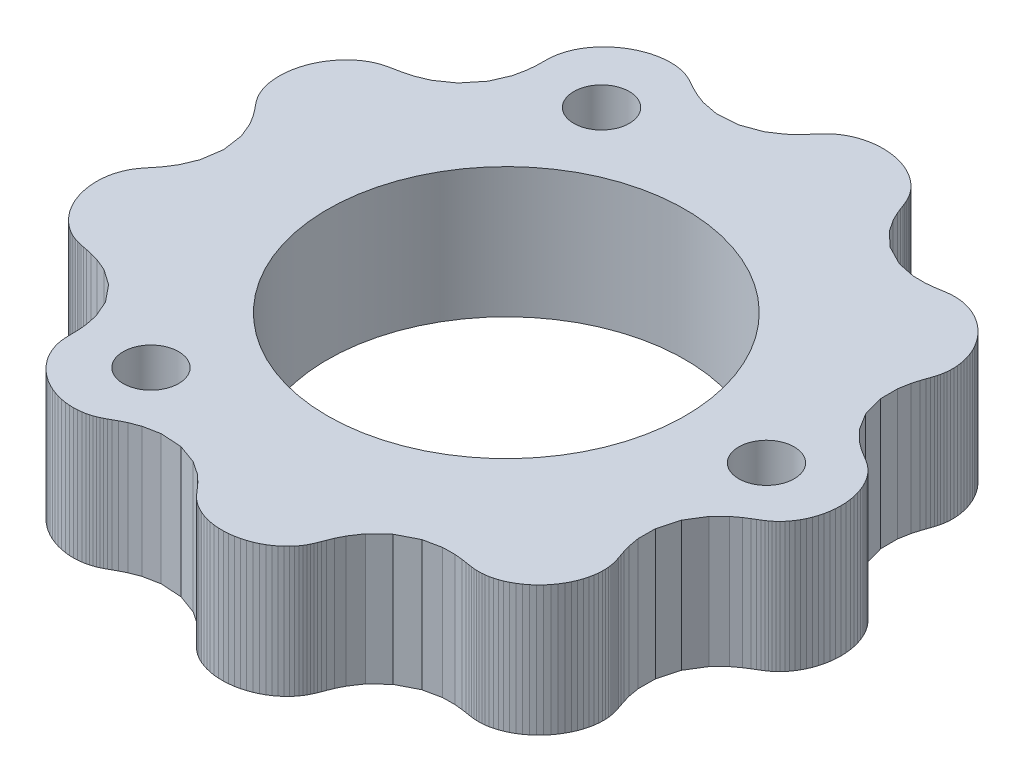
SolidWorks part; units mm, degrees
ref_plane "Front" through (0, 0, 0) normal (0, 0, 1) x (1, 0, 0)
ref_plane "Top" through (0, 0, 0) normal (0, 1, 0) x (1, 0, 0)
ref_plane "Right" through (0, 0, 0) normal (1, 0, 0) x (0, 0, -1)
sketch "Sketch1" plane through (0, 0, 0) normal (0, 1, 0) x (1, 0, 0)
  line L0 (15.113, 0) -> (15.1037, 0.2524) construction
  line L1 (15.1037, 0.2524) -> (15.0761, 0.5014) construction
  line L2 (15.0761, 0.5014) -> (15.0311, 0.744) construction
  line L3 (15.0311, 0.744) -> (14.9699, 0.9771) construction
  line L4 (14.9699, 0.9771) -> (14.8944, 1.198) construction
  line L5 (14.8944, 1.198) -> (14.8069, 1.4044) construction
  line L6 (14.8069, 1.4044) -> (14.7097, 1.5946) construction
  line L7 (14.7097, 1.5946) -> (14.6056, 1.7674) construction
  line L8 (14.6056, 1.7674) -> (14.4973, 1.922) construction
  line L9 (14.4973, 1.922) -> (14.3874, 2.0586) construction
  line L10 (14.3874, 2.0586) -> (14.2779, 2.1778) construction
  line L11 (14.2779, 2.1778) -> (14.1706, 2.2811) construction
  line L12 (14.1706, 2.2811) -> (14.0658, 2.3708) construction
  line L13 (14.0658, 2.3708) -> (13.9626, 2.4499) construction
  line L14 (13.9626, 2.4499) -> (13.8577, 2.5227) construction
  line L15 (13.8577, 2.5227) -> (13.7444, 2.5952) construction
  line L16 (13.7444, 2.5952) -> (13.6106, 2.6762) construction
  line L17 (13.6106, 2.6762) -> (13.4356, 2.7811) construction
  line L18 (13.4356, 2.7811) -> (13.1874, 2.9387) construction
  line L19 (13.1874, 2.9387) -> (12.8245, 3.2087) construction
  line L20 (12.8245, 3.2087) -> (12.3314, 3.7011) construction
  line L21 (12.3314, 3.7011) -> (11.8258, 4.5171) construction
  line L22 (11.8258, 4.5171) -> (11.5537, 5.5075) construction
  line L23 (11.5537, 5.5075) -> (11.55, 6.3294) construction
  line L24 (11.55, 6.3294) -> (11.6479, 6.8716) construction
  line L25 (11.6479, 6.8716) -> (11.7462, 7.2119) construction
  line L26 (11.7462, 7.2119) -> (11.8222, 7.4368) construction
  line L27 (11.8222, 7.4368) -> (11.879, 7.6008) construction
  line L28 (11.879, 7.6008) -> (11.9232, 7.7357) construction
  line L29 (11.9232, 7.7357) -> (11.9594, 7.8598) construction
  line L30 (11.9594, 7.8598) -> (11.9899, 7.9842) construction
  line L31 (11.9899, 7.9842) -> (12.0151, 8.1157) construction
  line L32 (12.0151, 8.1157) -> (12.0342, 8.2582) construction
  line L33 (12.0342, 8.2582) -> (12.0455, 8.4138) construction
  line L34 (12.0455, 8.4138) -> (12.047, 8.5831) construction
  line L35 (12.047, 8.5831) -> (12.0365, 8.7657) construction
  line L36 (12.0365, 8.7657) -> (12.012, 8.9602) construction
  line L37 (12.012, 8.9602) -> (11.9717, 9.1647) construction
  line L38 (11.9717, 9.1647) -> (11.9141, 9.3767) construction
  line L39 (11.9141, 9.3767) -> (11.8383, 9.5933) construction
  line L40 (11.8383, 9.5933) -> (11.7436, 9.8115) construction
  line L41 (11.7436, 9.8115) -> (11.6304, 10.0281) construction
  line L42 (11.6304, 10.0281) -> (11.4991, 10.2398) construction
  line L43 (11.4991, 10.2398) -> (11.3509, 10.4435) construction
  line L44 (11.3509, 10.4435) -> (11.1876, 10.6365) construction
  line L45 (11.1876, 10.6365) -> (11.0114, 10.8162) construction
  line L46 (11.0114, 10.8162) -> (10.8247, 10.9805) construction
  line L47 (10.8247, 10.9805) -> (10.6304, 11.1277) construction
  line L48 (10.6304, 11.1277) -> (10.4316, 11.2567) construction
  line L49 (10.4316, 11.2567) -> (10.2314, 11.3669) construction
  line L50 (10.2314, 11.3669) -> (10.033, 11.4584) construction
  line L51 (10.033, 11.4584) -> (9.8393, 11.5316) construction
  line L52 (9.8393, 11.5316) -> (9.6529, 11.5876) construction
  line L53 (9.6529, 11.5876) -> (9.4761, 11.628) construction
  line L54 (9.4761, 11.628) -> (9.3104, 11.6545) construction
  line L55 (9.3104, 11.6545) -> (9.1565, 11.6691) construction
  line L56 (9.1565, 11.6691) -> (9.0141, 11.6741) construction
  line L57 (9.0141, 11.6741) -> (8.8811, 11.6714) construction
  line L58 (8.8811, 11.6714) -> (8.7536, 11.6623) construction
  line L59 (8.7536, 11.6623) -> (8.6244, 11.6475) construction
  line L60 (8.6244, 11.6475) -> (8.4816, 11.6267) construction
  line L61 (8.4816, 11.6267) -> (8.305, 11.5984) construction
  line L62 (8.305, 11.5984) -> (8.0605, 11.5618) construction
  line L63 (8.0605, 11.5618) -> (7.6906, 11.5252) construction
  line L64 (7.6906, 11.5252) -> (7.1123, 11.532) construction
  line L65 (7.1123, 11.532) -> (6.2778, 11.7054) construction
  line L66 (6.2778, 11.7054) -> (5.3573, 12.1787) construction
  line L67 (5.3573, 12.1787) -> (4.6782, 12.8227) construction
  line L68 (4.6782, 12.8227) -> (4.3077, 13.3763) construction
  line L69 (4.3077, 13.3763) -> (4.1189, 13.7632) construction
  line L70 (4.1189, 13.7632) -> (4.013, 14.0236) construction
  line L71 (4.013, 14.0236) -> (3.9428, 14.2077) construction
  line L72 (3.9428, 14.2077) -> (3.8871, 14.3502) construction
  line L73 (3.8871, 14.3502) -> (3.8355, 14.4729) construction
  line L74 (3.8355, 14.4729) -> (3.7815, 14.5885) construction
  line L75 (3.7815, 14.5885) -> (3.7206, 14.7041) construction
  line L76 (3.7206, 14.7041) -> (3.6492, 14.8234) construction
  line L77 (3.6492, 14.8234) -> (3.5645, 14.9476) construction
  line L78 (3.5645, 14.9476) -> (3.4642, 15.0766) construction
  line L79 (3.4642, 15.0766) -> (3.3469, 15.2088) construction
  line L80 (3.3469, 15.2088) -> (3.2113, 15.3424) construction
  line L81 (3.2113, 15.3424) -> (3.0572, 15.4746) construction
  line L82 (3.0572, 15.4746) -> (2.8848, 15.6027) construction
  line L83 (2.8848, 15.6027) -> (2.6948, 15.7239) construction
  line L84 (2.6948, 15.7239) -> (2.4886, 15.8353) construction
  line L85 (2.4886, 15.8353) -> (2.2682, 15.9346) construction
  line L86 (2.2682, 15.9346) -> (2.036, 16.0194) construction
  line L87 (2.036, 16.0194) -> (1.7946, 16.0879) construction
  line L88 (1.7946, 16.0879) -> (1.5472, 16.1389) construction
  line L89 (1.5472, 16.1389) -> (1.2969, 16.1715) construction
  line L90 (1.2969, 16.1715) -> (1.047, 16.1855) construction
  line L91 (1.047, 16.1855) -> (0.8009, 16.1813) construction
  line L92 (0.8009, 16.1813) -> (0.5617, 16.1596) construction
  line L93 (0.5617, 16.1596) -> (0.3322, 16.1219) construction
  line L94 (0.3322, 16.1219) -> (0.1152, 16.0701) construction
  line L95 (0.1152, 16.0701) -> (-0.0873, 16.0062) construction
  line L96 (-0.0873, 16.0062) -> (-0.2736, 15.9328) construction
  line L97 (-0.2736, 15.9328) -> (-0.4428, 15.8523) construction
  line L98 (-0.4428, 15.8523) -> (-0.5944, 15.7674) construction
  line L99 (-0.5944, 15.7674) -> (-0.729, 15.6802) construction
  line L100 (-0.729, 15.6802) -> (-0.8477, 15.5923) construction
  line L101 (-0.8477, 15.5923) -> (-0.9528, 15.5047) construction
  line L102 (-0.9528, 15.5047) -> (-1.0477, 15.4167) construction
  line L103 (-1.0477, 15.4167) -> (-1.1374, 15.3255) construction
  line L104 (-1.1374, 15.3255) -> (-1.2291, 15.2251) construction
  line L105 (-1.2291, 15.2251) -> (-1.3345, 15.1043) construction
  line L106 (-1.3345, 15.1043) -> (-1.4732, 14.9447) construction
  line L107 (-1.4732, 14.9447) -> (-1.682, 14.7187) construction
  line L108 (-1.682, 14.7187) -> (-2.0315, 14.3967) construction
  line L109 (-2.0315, 14.3967) -> (-2.6365, 13.9915) construction
  line L110 (-2.6365, 13.9915) -> (-3.5585, 13.6551) construction
  line L111 (-3.5585, 13.6551) -> (-4.5719, 13.5925) construction
  line L112 (-4.5719, 13.5925) -> (-5.3478, 13.7456) construction
  line L113 (-5.3478, 13.7456) -> (-5.8372, 13.9345) construction
  line L114 (-5.8372, 13.9345) -> (-6.1394, 14.0854) construction
  line L115 (-6.1394, 14.0854) -> (-6.3393, 14.1953) construction
  line L116 (-6.3393, 14.1953) -> (-6.4869, 14.2772) construction
  line L117 (-6.4869, 14.2772) -> (-6.6103, 14.3428) construction
  line L118 (-6.6103, 14.3428) -> (-6.726, 14.3992) construction
  line L119 (-6.726, 14.3992) -> (-6.8438, 14.4504) construction
  line L120 (-6.8438, 14.4504) -> (-6.9701, 14.4976) construction
  line L121 (-6.9701, 14.4976) -> (-7.1086, 14.5406) construction
  line L122 (-7.1086, 14.5406) -> (-7.2615, 14.5781) construction
  line L123 (-7.2615, 14.5781) -> (-7.4297, 14.608) construction
  line L124 (-7.4297, 14.608) -> (-7.6129, 14.6282) construction
  line L125 (-7.6129, 14.6282) -> (-7.8102, 14.6364) construction
  line L126 (-7.8102, 14.6364) -> (-8.0199, 14.6306) construction
  line L127 (-8.0199, 14.6306) -> (-8.2397, 14.6088) construction
  line L128 (-8.2397, 14.6088) -> (-8.4669, 14.5697) construction
  line L129 (-8.4669, 14.5697) -> (-8.6986, 14.5124) construction
  line L130 (-8.6986, 14.5124) -> (-8.9315, 14.4364) construction
  line L131 (-8.9315, 14.4364) -> (-9.1623, 14.3418) construction
  line L132 (-9.1623, 14.3418) -> (-9.388, 14.2293) construction
  line L133 (-9.388, 14.2293) -> (-9.6053, 14.1003) construction
  line L134 (-9.6053, 14.1003) -> (-9.8115, 13.9564) construction
  line L135 (-9.8115, 13.9564) -> (-10.0041, 13.7997) construction
  line L136 (-10.0041, 13.7997) -> (-10.1809, 13.633) construction
  line L137 (-10.1809, 13.633) -> (-10.3405, 13.4589) construction
  line L138 (-10.3405, 13.4589) -> (-10.4818, 13.2806) construction
  line L139 (-10.4818, 13.2806) -> (-10.6042, 13.1011) construction
  line L140 (-10.6042, 13.1011) -> (-10.7079, 12.9234) construction
  line L141 (-10.7079, 12.9234) -> (-10.7935, 12.7502) construction
  line L142 (-10.7935, 12.7502) -> (-10.8621, 12.5839) construction
  line L143 (-10.8621, 12.5839) -> (-10.9154, 12.4264) construction
  line L144 (-10.9154, 12.4264) -> (-10.9551, 12.2785) construction
  line L145 (-10.9551, 12.2785) -> (-10.9837, 12.1401) construction
  line L146 (-10.9837, 12.1401) -> (-11.0031, 12.0093) construction
  line L147 (-11.0031, 12.0093) -> (-11.0156, 11.8823) construction
  line L148 (-11.0156, 11.8823) -> (-11.0231, 11.7516) construction
  line L149 (-11.0231, 11.7516) -> (-11.0271, 11.6047) construction
  line L150 (-11.0271, 11.6047) -> (-11.0299, 11.4203) construction
  line L151 (-11.0299, 11.4203) -> (-11.0374, 11.1626) construction
  line L152 (-11.0374, 11.1626) -> (-11.0704, 10.7738) construction
  line L153 (-11.0704, 10.7738) -> (-11.193, 10.1795) construction
  line L154 (-11.193, 10.1795) -> (-11.5414, 9.3696) construction
  line L155 (-11.5414, 9.3696) -> (-12.1963, 8.5629) construction
  line L156 (-12.1963, 8.5629) -> (-12.9426, 8.0428) construction
  line L157 (-12.9426, 8.0428) -> (-13.5295, 7.7974) construction
  line L158 (-13.5295, 7.7974) -> (-13.9245, 7.6885) construction
  line L159 (-13.9245, 7.6885) -> (-14.1879, 7.6331) construction
  line L160 (-14.1879, 7.6331) -> (-14.3749, 7.5972) construction
  line L161 (-14.3749, 7.5972) -> (-14.5218, 7.5675) construction
  line L162 (-14.5218, 7.5675) -> (-14.6503, 7.5377) construction
  line L163 (-14.6503, 7.5377) -> (-14.7733, 7.504) construction
  line L164 (-14.7733, 7.504) -> (-14.8982, 7.4631) construction
  line L165 (-14.8982, 7.4631) -> (-15.0288, 7.4122) construction
  line L166 (-15.0288, 7.4122) -> (-15.1667, 7.3489) construction
  line L167 (-15.1667, 7.3489) -> (-15.3119, 7.2709) construction
  line L168 (-15.3119, 7.2709) -> (-15.4631, 7.1764) construction
  line L169 (-15.4631, 7.1764) -> (-15.6185, 7.064) construction
  line L170 (-15.6185, 7.064) -> (-15.7755, 6.9331) construction
  line L171 (-15.7755, 6.9331) -> (-15.9313, 6.7835) construction
  line L172 (-15.9313, 6.7835) -> (-16.0831, 6.6154) construction
  line L173 (-16.0831, 6.6154) -> (-16.2277, 6.4298) construction
  line L174 (-16.2277, 6.4298) -> (-16.3625, 6.2284) construction
  line L175 (-16.3625, 6.2284) -> (-16.4848, 6.0129) construction
  line L176 (-16.4848, 6.0129) -> (-16.5925, 5.786) construction
  line L177 (-16.5925, 5.786) -> (-16.6838, 5.5503) construction
  line L178 (-16.6838, 5.5503) -> (-16.7573, 5.309) construction
  line L179 (-16.7573, 5.309) -> (-16.8125, 5.0653) construction
  line L180 (-16.8125, 5.0653) -> (-16.849, 4.8224) construction
  line L181 (-16.849, 4.8224) -> (-16.8672, 4.5837) construction
  line L182 (-16.8672, 4.5837) -> (-16.8681, 4.3522) construction
  line L183 (-16.8681, 4.3522) -> (-16.853, 4.1307) construction
  line L184 (-16.853, 4.1307) -> (-16.8238, 3.9216) construction
  line L185 (-16.8238, 3.9216) -> (-16.7826, 3.7271) construction
  line L186 (-16.7826, 3.7271) -> (-16.7318, 3.5483) construction
  line L187 (-16.7318, 3.5483) -> (-16.6738, 3.3861) construction
  line L188 (-16.6738, 3.3861) -> (-16.6108, 3.2402) construction
  line L189 (-16.6108, 3.2402) -> (-16.5447, 3.1096) construction
  line L190 (-16.5447, 3.1096) -> (-16.4764, 2.9922) construction
  line L191 (-16.4764, 2.9922) -> (-16.4059, 2.8843) construction
  line L192 (-16.4059, 2.8843) -> (-16.331, 2.7802) construction
  line L193 (-16.331, 2.7802) -> (-16.2466, 2.6713) construction
  line L194 (-16.2466, 2.6713) -> (-16.1432, 2.5436) construction
  line L195 (-16.1432, 2.5436) -> (-16.0053, 2.3728) construction
  line L196 (-16.0053, 2.3728) -> (-15.8117, 2.1151) construction
  line L197 (-15.8117, 2.1151) -> (-15.5478, 1.6912) construction
  line L198 (-15.5478, 1.6912) -> (-15.2569, 0.9896) construction
  line L199 (-15.2569, 0.9896) -> (-15.113, 0) construction
  line L200 (-15.113, 0) -> (-15.2569, -0.9896) construction
  line L201 (-15.2569, -0.9896) -> (-15.5478, -1.6912) construction
  line L202 (-15.5478, -1.6912) -> (-15.8117, -2.1151) construction
  line L203 (-15.8117, -2.1151) -> (-16.0053, -2.3728) construction
  line L204 (-16.0053, -2.3728) -> (-16.1432, -2.5436) construction
  line L205 (-16.1432, -2.5436) -> (-16.2466, -2.6713) construction
  line L206 (-16.2466, -2.6713) -> (-16.331, -2.7802) construction
  line L207 (-16.331, -2.7802) -> (-16.4059, -2.8843) construction
  line L208 (-16.4059, -2.8843) -> (-16.4764, -2.9922) construction
  line L209 (-16.4764, -2.9922) -> (-16.5447, -3.1096) construction
  line L210 (-16.5447, -3.1096) -> (-16.6108, -3.2402) construction
  line L211 (-16.6108, -3.2402) -> (-16.6738, -3.3861) construction
  line L212 (-16.6738, -3.3861) -> (-16.7318, -3.5483) construction
  line L213 (-16.7318, -3.5483) -> (-16.7826, -3.7271) construction
  line L214 (-16.7826, -3.7271) -> (-16.8238, -3.9216) construction
  line L215 (-16.8238, -3.9216) -> (-16.853, -4.1307) construction
  line L216 (-16.853, -4.1307) -> (-16.8681, -4.3522) construction
  line L217 (-16.8681, -4.3522) -> (-16.8672, -4.5837) construction
  line L218 (-16.8672, -4.5837) -> (-16.849, -4.8224) construction
  line L219 (-16.849, -4.8224) -> (-16.8125, -5.0653) construction
  line L220 (-16.8125, -5.0653) -> (-16.7573, -5.309) construction
  line L221 (-16.7573, -5.309) -> (-16.6838, -5.5503) construction
  line L222 (-16.6838, -5.5503) -> (-16.5925, -5.786) construction
  line L223 (-16.5925, -5.786) -> (-16.4848, -6.0129) construction
  line L224 (-16.4848, -6.0129) -> (-16.3625, -6.2284) construction
  line L225 (-16.3625, -6.2284) -> (-16.2277, -6.4298) construction
  line L226 (-16.2277, -6.4298) -> (-16.0831, -6.6154) construction
  line L227 (-16.0831, -6.6154) -> (-15.9313, -6.7835) construction
  line L228 (-15.9313, -6.7835) -> (-15.7755, -6.9331) construction
  line L229 (-15.7755, -6.9331) -> (-15.6185, -7.064) construction
  line L230 (-15.6185, -7.064) -> (-15.4631, -7.1764) construction
  line L231 (-15.4631, -7.1764) -> (-15.3119, -7.2709) construction
  line L232 (-15.3119, -7.2709) -> (-15.1667, -7.3489) construction
  line L233 (-15.1667, -7.3489) -> (-15.0288, -7.4122) construction
  line L234 (-15.0288, -7.4122) -> (-14.8982, -7.4631) construction
  line L235 (-14.8982, -7.4631) -> (-14.7733, -7.504) construction
  line L236 (-14.7733, -7.504) -> (-14.6503, -7.5377) construction
  line L237 (-14.6503, -7.5377) -> (-14.5218, -7.5675) construction
  line L238 (-14.5218, -7.5675) -> (-14.3749, -7.5972) construction
  line L239 (-14.3749, -7.5972) -> (-14.1879, -7.6331) construction
  line L240 (-14.1879, -7.6331) -> (-13.9245, -7.6885) construction
  line L241 (-13.9245, -7.6885) -> (-13.5295, -7.7974) construction
  line L242 (-13.5295, -7.7974) -> (-12.9426, -8.0428) construction
  line L243 (-12.9426, -8.0428) -> (-12.1963, -8.5629) construction
  line L244 (-12.1963, -8.5629) -> (-11.5414, -9.3696) construction
  line L245 (-11.5414, -9.3696) -> (-11.193, -10.1795) construction
  line L246 (-11.193, -10.1795) -> (-11.0704, -10.7738) construction
  line L247 (-11.0704, -10.7738) -> (-11.0374, -11.1626) construction
  line L248 (-11.0374, -11.1626) -> (-11.0299, -11.4203) construction
  line L249 (-11.0299, -11.4203) -> (-11.0271, -11.6047) construction
  line L250 (-11.0271, -11.6047) -> (-11.0231, -11.7516) construction
  line L251 (-11.0231, -11.7516) -> (-11.0156, -11.8823) construction
  line L252 (-11.0156, -11.8823) -> (-11.0031, -12.0093) construction
  line L253 (-11.0031, -12.0093) -> (-10.9837, -12.1401) construction
  line L254 (-10.9837, -12.1401) -> (-10.9551, -12.2785) construction
  line L255 (-10.9551, -12.2785) -> (-10.9154, -12.4264) construction
  line L256 (-10.9154, -12.4264) -> (-10.8621, -12.5839) construction
  line L257 (-10.8621, -12.5839) -> (-10.7935, -12.7502) construction
  line L258 (-10.7935, -12.7502) -> (-10.7079, -12.9234) construction
  line L259 (-10.7079, -12.9234) -> (-10.6042, -13.1011) construction
  line L260 (-10.6042, -13.1011) -> (-10.4818, -13.2806) construction
  line L261 (-10.4818, -13.2806) -> (-10.3405, -13.4589) construction
  line L262 (-10.3405, -13.4589) -> (-10.1809, -13.633) construction
  line L263 (-10.1809, -13.633) -> (-10.0041, -13.7997) construction
  line L264 (-10.0041, -13.7997) -> (-9.8115, -13.9564) construction
  line L265 (-9.8115, -13.9564) -> (-9.6053, -14.1003) construction
  line L266 (-9.6053, -14.1003) -> (-9.388, -14.2293) construction
  line L267 (-9.388, -14.2293) -> (-9.1623, -14.3418) construction
  line L268 (-9.1623, -14.3418) -> (-8.9315, -14.4364) construction
  line L269 (-8.9315, -14.4364) -> (-8.6986, -14.5124) construction
  line L270 (-8.6986, -14.5124) -> (-8.4669, -14.5697) construction
  line L271 (-8.4669, -14.5697) -> (-8.2397, -14.6088) construction
  line L272 (-8.2397, -14.6088) -> (-8.0199, -14.6306) construction
  line L273 (-8.0199, -14.6306) -> (-7.8102, -14.6364) construction
  line L274 (-7.8102, -14.6364) -> (-7.6129, -14.6282) construction
  line L275 (-7.6129, -14.6282) -> (-7.4297, -14.608) construction
  line L276 (-7.4297, -14.608) -> (-7.2615, -14.5781) construction
  line L277 (-7.2615, -14.5781) -> (-7.1086, -14.5406) construction
  line L278 (-7.1086, -14.5406) -> (-6.9701, -14.4976) construction
  line L279 (-6.9701, -14.4976) -> (-6.8438, -14.4504) construction
  line L280 (-6.8438, -14.4504) -> (-6.726, -14.3992) construction
  line L281 (-6.726, -14.3992) -> (-6.6103, -14.3428) construction
  line L282 (-6.6103, -14.3428) -> (-6.4869, -14.2772) construction
  line L283 (-6.4869, -14.2772) -> (-6.3393, -14.1953) construction
  line L284 (-6.3393, -14.1953) -> (-6.1394, -14.0854) construction
  line L285 (-6.1394, -14.0854) -> (-5.8372, -13.9345) construction
  line L286 (-5.8372, -13.9345) -> (-5.3478, -13.7456) construction
  line L287 (-5.3478, -13.7456) -> (-4.5719, -13.5925) construction
  line L288 (-4.5719, -13.5925) -> (-3.5585, -13.6551) construction
  line L289 (-3.5585, -13.6551) -> (-2.6365, -13.9915) construction
  line L290 (-2.6365, -13.9915) -> (-2.0315, -14.3967) construction
  line L291 (-2.0315, -14.3967) -> (-1.682, -14.7187) construction
  line L292 (-1.682, -14.7187) -> (-1.4732, -14.9447) construction
  line L293 (-1.4732, -14.9447) -> (-1.3345, -15.1043) construction
  line L294 (-1.3345, -15.1043) -> (-1.2291, -15.2251) construction
  line L295 (-1.2291, -15.2251) -> (-1.1374, -15.3255) construction
  line L296 (-1.1374, -15.3255) -> (-1.0477, -15.4167) construction
  line L297 (-1.0477, -15.4167) -> (-0.9528, -15.5047) construction
  line L298 (-0.9528, -15.5047) -> (-0.8477, -15.5923) construction
  line L299 (-0.8477, -15.5923) -> (-0.729, -15.6802) construction
  line L300 (-0.729, -15.6802) -> (-0.5944, -15.7674) construction
  line L301 (-0.5944, -15.7674) -> (-0.4428, -15.8523) construction
  line L302 (-0.4428, -15.8523) -> (-0.2736, -15.9328) construction
  line L303 (-0.2736, -15.9328) -> (-0.0873, -16.0062) construction
  line L304 (-0.0873, -16.0062) -> (0.1152, -16.0701) construction
  line L305 (0.1152, -16.0701) -> (0.3322, -16.1219) construction
  line L306 (0.3322, -16.1219) -> (0.5617, -16.1596) construction
  line L307 (0.5617, -16.1596) -> (0.8009, -16.1813) construction
  line L308 (0.8009, -16.1813) -> (1.047, -16.1855) construction
  line L309 (1.047, -16.1855) -> (1.2969, -16.1715) construction
  line L310 (1.2969, -16.1715) -> (1.5472, -16.1389) construction
  line L311 (1.5472, -16.1389) -> (1.7946, -16.0879) construction
  line L312 (1.7946, -16.0879) -> (2.036, -16.0194) construction
  line L313 (2.036, -16.0194) -> (2.2682, -15.9346) construction
  line L314 (2.2682, -15.9346) -> (2.4886, -15.8353) construction
  line L315 (2.4886, -15.8353) -> (2.6948, -15.7239) construction
  line L316 (2.6948, -15.7239) -> (2.8848, -15.6027) construction
  line L317 (2.8848, -15.6027) -> (3.0572, -15.4746) construction
  line L318 (3.0572, -15.4746) -> (3.2113, -15.3424) construction
  line L319 (3.2113, -15.3424) -> (3.3469, -15.2088) construction
  line L320 (3.3469, -15.2088) -> (3.4642, -15.0766) construction
  line L321 (3.4642, -15.0766) -> (3.5645, -14.9476) construction
  line L322 (3.5645, -14.9476) -> (3.6492, -14.8234) construction
  line L323 (3.6492, -14.8234) -> (3.7206, -14.7041) construction
  line L324 (3.7206, -14.7041) -> (3.7815, -14.5885) construction
  line L325 (3.7815, -14.5885) -> (3.8355, -14.4729) construction
  line L326 (3.8355, -14.4729) -> (3.8871, -14.3502) construction
  line L327 (3.8871, -14.3502) -> (3.9428, -14.2077) construction
  line L328 (3.9428, -14.2077) -> (4.013, -14.0236) construction
  line L329 (4.013, -14.0236) -> (4.1189, -13.7632) construction
  line L330 (4.1189, -13.7632) -> (4.3077, -13.3763) construction
  line L331 (4.3077, -13.3763) -> (4.6782, -12.8227) construction
  line L332 (4.6782, -12.8227) -> (5.3573, -12.1787) construction
  line L333 (5.3573, -12.1787) -> (6.2778, -11.7054) construction
  line L334 (6.2778, -11.7054) -> (7.1123, -11.532) construction
  line L335 (7.1123, -11.532) -> (7.6906, -11.5252) construction
  line L336 (7.6906, -11.5252) -> (8.0605, -11.5618) construction
  line L337 (8.0605, -11.5618) -> (8.305, -11.5984) construction
  line L338 (8.305, -11.5984) -> (8.4816, -11.6267) construction
  line L339 (8.4816, -11.6267) -> (8.6244, -11.6475) construction
  line L340 (8.6244, -11.6475) -> (8.7536, -11.6623) construction
  line L341 (8.7536, -11.6623) -> (8.8811, -11.6714) construction
  line L342 (8.8811, -11.6714) -> (9.0141, -11.6741) construction
  line L343 (9.0141, -11.6741) -> (9.1565, -11.6691) construction
  line L344 (9.1565, -11.6691) -> (9.3104, -11.6545) construction
  line L345 (9.3104, -11.6545) -> (9.4761, -11.628) construction
  line L346 (9.4761, -11.628) -> (9.6529, -11.5876) construction
  line L347 (9.6529, -11.5876) -> (9.8393, -11.5316) construction
  line L348 (9.8393, -11.5316) -> (10.033, -11.4584) construction
  line L349 (10.033, -11.4584) -> (10.2314, -11.3669) construction
  line L350 (10.2314, -11.3669) -> (10.4316, -11.2567) construction
  line L351 (10.4316, -11.2567) -> (10.6304, -11.1277) construction
  line L352 (10.6304, -11.1277) -> (10.8247, -10.9805) construction
  line L353 (10.8247, -10.9805) -> (11.0114, -10.8162) construction
  line L354 (11.0114, -10.8162) -> (11.1876, -10.6365) construction
  line L355 (11.1876, -10.6365) -> (11.3509, -10.4435) construction
  line L356 (11.3509, -10.4435) -> (11.4991, -10.2398) construction
  line L357 (11.4991, -10.2398) -> (11.6304, -10.0281) construction
  line L358 (11.6304, -10.0281) -> (11.7436, -9.8115) construction
  line L359 (11.7436, -9.8115) -> (11.8383, -9.5933) construction
  line L360 (11.8383, -9.5933) -> (11.9141, -9.3767) construction
  line L361 (11.9141, -9.3767) -> (11.9717, -9.1647) construction
  line L362 (11.9717, -9.1647) -> (12.012, -8.9602) construction
  line L363 (12.012, -8.9602) -> (12.0365, -8.7657) construction
  line L364 (12.0365, -8.7657) -> (12.047, -8.5831) construction
  line L365 (12.047, -8.5831) -> (12.0455, -8.4138) construction
  line L366 (12.0455, -8.4138) -> (12.0342, -8.2582) construction
  line L367 (12.0342, -8.2582) -> (12.0151, -8.1157) construction
  line L368 (12.0151, -8.1157) -> (11.9899, -7.9842) construction
  line L369 (11.9899, -7.9842) -> (11.9594, -7.8598) construction
  line L370 (11.9594, -7.8598) -> (11.9232, -7.7357) construction
  line L371 (11.9232, -7.7357) -> (11.879, -7.6008) construction
  line L372 (11.879, -7.6008) -> (11.8222, -7.4368) construction
  line L373 (11.8222, -7.4368) -> (11.7462, -7.2119) construction
  line L374 (11.7462, -7.2119) -> (11.6479, -6.8716) construction
  line L375 (11.6479, -6.8716) -> (11.55, -6.3294) construction
  line L376 (11.55, -6.3294) -> (11.5537, -5.5075) construction
  line L377 (11.5537, -5.5075) -> (11.8258, -4.5171) construction
  line L378 (11.8258, -4.5171) -> (12.3314, -3.7011) construction
  line L379 (12.3314, -3.7011) -> (12.8245, -3.2087) construction
  line L380 (12.8245, -3.2087) -> (13.1874, -2.9387) construction
  line L381 (13.1874, -2.9387) -> (13.4356, -2.7811) construction
  line L382 (13.4356, -2.7811) -> (13.6106, -2.6762) construction
  line L383 (13.6106, -2.6762) -> (13.7444, -2.5952) construction
  line L384 (13.7444, -2.5952) -> (13.8577, -2.5227) construction
  line L385 (13.8577, -2.5227) -> (13.9626, -2.4499) construction
  line L386 (13.9626, -2.4499) -> (14.0658, -2.3708) construction
  line L387 (14.0658, -2.3708) -> (14.1706, -2.2811) construction
  line L388 (14.1706, -2.2811) -> (14.2779, -2.1778) construction
  line L389 (14.2779, -2.1778) -> (14.3874, -2.0586) construction
  line L390 (14.3874, -2.0586) -> (14.4973, -1.922) construction
  line L391 (14.4973, -1.922) -> (14.6056, -1.7674) construction
  line L392 (14.6056, -1.7674) -> (14.7097, -1.5946) construction
  line L393 (14.7097, -1.5946) -> (14.8069, -1.4044) construction
  line L394 (14.8069, -1.4044) -> (14.8944, -1.198) construction
  line L395 (14.8944, -1.198) -> (14.9699, -0.9771) construction
  line L396 (14.9699, -0.9771) -> (15.0311, -0.744) construction
  line L397 (15.0311, -0.744) -> (15.0761, -0.5014) construction
  line L398 (15.0761, -0.5014) -> (15.1037, -0.2524) construction
  line L399 (15.1037, -0.2524) -> (15.113, 0) construction
  line L400 (13.1586, 2.8968) -> (12.7913, 3.1701)
  line L401 (12.7913, 3.1701) -> (12.2913, 3.6693)
  line L402 (12.2913, 3.6693) -> (11.7787, 4.4966)
  line L403 (11.7787, 4.4966) -> (11.5029, 5.5006)
  line L404 (11.5029, 5.5006) -> (11.4991, 6.3338)
  line L405 (11.4991, 6.3338) -> (11.5984, 6.8832)
  line L406 (11.5984, 6.8832) -> (11.6978, 7.2271)
  line L407 (11.6978, 7.2271) -> (11.7742, 7.4532)
  line L408 (11.7742, 7.4532) -> (11.8309, 7.6171)
  line L409 (11.8309, 7.6171) -> (11.8747, 7.7507)
  line L410 (11.8747, 7.7507) -> (11.9103, 7.873)
  line L411 (11.9103, 7.873) -> (11.9402, 7.9951)
  line L412 (11.9402, 7.9951) -> (11.9649, 8.1239)
  line L413 (11.9649, 8.1239) -> (11.9836, 8.2635)
  line L414 (11.9836, 8.2635) -> (11.9947, 8.4159)
  line L415 (11.9947, 8.4159) -> (11.9962, 8.5819)
  line L416 (11.9962, 8.5819) -> (11.9859, 8.7611)
  line L417 (11.9859, 8.7611) -> (11.9619, 8.9521)
  line L418 (11.9619, 8.9521) -> (11.9222, 9.1531)
  line L419 (11.9222, 9.1531) -> (11.8656, 9.3616)
  line L420 (11.8656, 9.3616) -> (11.7909, 9.5748)
  line L421 (11.7909, 9.5748) -> (11.6978, 9.7896)
  line L422 (11.6978, 9.7896) -> (11.5862, 10.0029)
  line L423 (11.5862, 10.0029) -> (11.4569, 10.2114)
  line L424 (11.4569, 10.2114) -> (11.3109, 10.4121)
  line L425 (11.3109, 10.4121) -> (11.1501, 10.6023)
  line L426 (11.1501, 10.6023) -> (10.9764, 10.7793)
  line L427 (10.9764, 10.7793) -> (10.7925, 10.9411)
  line L428 (10.7925, 10.9411) -> (10.6012, 11.086)
  line L429 (10.6012, 11.086) -> (10.4055, 11.213)
  line L430 (10.4055, 11.213) -> (10.2085, 11.3215)
  line L431 (10.2085, 11.3215) -> (10.0134, 11.4115)
  line L432 (10.0134, 11.4115) -> (9.8229, 11.4835)
  line L433 (9.8229, 11.4835) -> (9.6399, 11.5385)
  line L434 (9.6399, 11.5385) -> (9.4664, 11.5781)
  line L435 (9.4664, 11.5781) -> (9.304, 11.604)
  line L436 (9.304, 11.604) -> (9.1532, 11.6184)
  line L437 (9.1532, 11.6184) -> (9.0137, 11.6233)
  line L438 (9.0137, 11.6233) -> (8.8834, 11.6206)
  line L439 (8.8834, 11.6206) -> (8.7583, 11.6117)
  line L440 (8.7583, 11.6117) -> (8.631, 11.5972)
  line L441 (8.631, 11.5972) -> (8.4893, 11.5765)
  line L442 (8.4893, 11.5765) -> (8.3128, 11.5482)
  line L443 (8.3128, 11.5482) -> (8.0668, 11.5114)
  line L444 (8.0668, 11.5114) -> (7.6928, 11.4744)
  line L445 (7.6928, 11.4744) -> (7.1068, 11.4813)
  line L446 (7.1068, 11.4813) -> (6.2607, 11.6571)
  line L447 (6.2607, 11.6571) -> (5.3277, 12.1368)
  line L448 (5.3277, 12.1368) -> (4.6391, 12.7897)
  line L449 (4.6391, 12.7897) -> (4.2635, 13.3509)
  line L450 (4.2635, 13.3509) -> (4.0725, 13.7425)
  line L451 (4.0725, 13.7425) -> (3.9657, 14.005)
  line L452 (3.9657, 14.005) -> (3.8954, 14.1894)
  line L453 (3.8954, 14.1894) -> (3.8401, 14.3312)
  line L454 (3.8401, 14.3312) -> (3.7891, 14.4523)
  line L455 (3.7891, 14.4523) -> (3.736, 14.5659)
  line L456 (3.736, 14.5659) -> (3.6763, 14.6792)
  line L457 (3.6763, 14.6792) -> (3.6063, 14.796)
  line L458 (3.6063, 14.796) -> (3.5234, 14.9177)
  line L459 (3.5234, 14.9177) -> (3.4251, 15.0441)
  line L460 (3.4251, 15.0441) -> (3.31, 15.1738)
  line L461 (3.31, 15.1738) -> (3.1769, 15.3049)
  line L462 (3.1769, 15.3049) -> (3.0255, 15.4348)
  line L463 (3.0255, 15.4348) -> (2.8559, 15.5608)
  line L464 (2.8559, 15.5608) -> (2.669, 15.68)
  line L465 (2.669, 15.68) -> (2.4661, 15.7898)
  line L466 (2.4661, 15.7898) -> (2.2491, 15.8875)
  line L467 (2.2491, 15.8875) -> (2.0203, 15.971)
  line L468 (2.0203, 15.971) -> (1.7825, 16.0385)
  line L469 (1.7825, 16.0385) -> (1.5388, 16.0887)
  line L470 (1.5388, 16.0887) -> (1.2922, 16.1209)
  line L471 (1.2922, 16.1209) -> (1.046, 16.1347)
  line L472 (1.046, 16.1347) -> (0.8036, 16.1305)
  line L473 (0.8036, 16.1305) -> (0.5681, 16.1092)
  line L474 (0.5681, 16.1092) -> (0.3423, 16.0721)
  line L475 (0.3423, 16.0721) -> (0.1288, 16.0211)
  line L476 (0.1288, 16.0211) -> (-0.0703, 15.9583)
  line L477 (-0.0703, 15.9583) -> (-0.2534, 15.8862)
  line L478 (-0.2534, 15.8862) -> (-0.4194, 15.8072)
  line L479 (-0.4194, 15.8072) -> (-0.5682, 15.7239)
  line L480 (-0.5682, 15.7239) -> (-0.7, 15.6384)
  line L481 (-0.7, 15.6384) -> (-0.8163, 15.5524)
  line L482 (-0.8163, 15.5524) -> (-0.9193, 15.4666)
  line L483 (-0.9193, 15.4666) -> (-1.0123, 15.3803)
  line L484 (-1.0123, 15.3803) -> (-1.1005, 15.2906)
  line L485 (-1.1005, 15.2906) -> (-1.1912, 15.1912)
  line L486 (-1.1912, 15.1912) -> (-1.2962, 15.0709)
  line L487 (-1.2962, 15.0709) -> (-1.4354, 14.9108)
  line L488 (-1.4354, 14.9108) -> (-1.6461, 14.6827)
  line L489 (-1.6461, 14.6827) -> (-2, 14.3566)
  line L490 (-2, 14.3566) -> (-2.6133, 13.9459)
  line L491 (-2.6133, 13.9459) -> (-3.548, 13.6048)
  line L492 (-3.548, 13.6048) -> (-4.5753, 13.5414)
  line L493 (-4.5753, 13.5414) -> (-5.362, 13.6966)
  line L494 (-5.362, 13.6966) -> (-5.8577, 13.888)
  line L495 (-5.8577, 13.888) -> (-6.163, 14.0404)
  line L496 (-6.163, 14.0404) -> (-6.3639, 14.1508)
  line L497 (-6.3639, 14.1508) -> (-6.5111, 14.2326)
  line L498 (-6.5111, 14.2326) -> (-6.6334, 14.2975)
  line L499 (-6.6334, 14.2975) -> (-6.7472, 14.3531)
  line L500 (-6.7472, 14.3531) -> (-6.8628, 14.4033)
  line L501 (-6.8628, 14.4033) -> (-6.9865, 14.4495)
  line L502 (-6.9865, 14.4495) -> (-7.1222, 14.4916)
  line L503 (-7.1222, 14.4916) -> (-7.272, 14.5283)
  line L504 (-7.272, 14.5283) -> (-7.4369, 14.5577)
  line L505 (-7.4369, 14.5577) -> (-7.6168, 14.5775)
  line L506 (-7.6168, 14.5775) -> (-7.8106, 14.5856)
  line L507 (-7.8106, 14.5856) -> (-8.0167, 14.5799)
  line L508 (-8.0167, 14.5799) -> (-8.2329, 14.5585)
  line L509 (-8.2329, 14.5585) -> (-8.4565, 14.52)
  line L510 (-8.4565, 14.52) -> (-8.6845, 14.4635)
  line L511 (-8.6845, 14.4635) -> (-8.9139, 14.3887)
  line L512 (-8.9139, 14.3887) -> (-9.1414, 14.2955)
  line L513 (-9.1414, 14.2955) -> (-9.3637, 14.1847)
  line L514 (-9.3637, 14.1847) -> (-9.5778, 14.0576)
  line L515 (-9.5778, 14.0576) -> (-9.7809, 13.9158)
  line L516 (-9.7809, 13.9158) -> (-9.9706, 13.7615)
  line L517 (-9.9706, 13.7615) -> (-10.1447, 13.5973)
  line L518 (-10.1447, 13.5973) -> (-10.3018, 13.4259)
  line L519 (-10.3018, 13.4259) -> (-10.4408, 13.2505)
  line L520 (-10.4408, 13.2505) -> (-10.5612, 13.0739)
  line L521 (-10.5612, 13.0739) -> (-10.6632, 12.8993)
  line L522 (-10.6632, 12.8993) -> (-10.7472, 12.7292)
  line L523 (-10.7472, 12.7292) -> (-10.8145, 12.5661)
  line L524 (-10.8145, 12.5661) -> (-10.8667, 12.4116)
  line L525 (-10.8667, 12.4116) -> (-10.9057, 12.2668)
  line L526 (-10.9057, 12.2668) -> (-10.9336, 12.1312)
  line L527 (-10.9336, 12.1312) -> (-10.9527, 12.0031)
  line L528 (-10.9527, 12.0031) -> (-10.965, 11.8784)
  line L529 (-10.965, 11.8784) -> (-10.9723, 11.7495)
  line L530 (-10.9723, 11.7495) -> (-10.9763, 11.6036)
  line L531 (-10.9763, 11.6036) -> (-10.9791, 11.4192)
  line L532 (-10.9791, 11.4192) -> (-10.9867, 11.1597)
  line L533 (-10.9867, 11.1597) -> (-11.0201, 10.7665)
  line L534 (-11.0201, 10.7665) -> (-11.1443, 10.1642)
  line L535 (-11.1443, 10.1642) -> (-11.4976, 9.3431)
  line L536 (-11.4976, 9.3431) -> (-12.1614, 8.5253)
  line L537 (-12.1614, 8.5253) -> (-12.918, 7.998)
  line L538 (-12.918, 7.998) -> (-13.5129, 7.7493)
  line L539 (-13.5129, 7.7493) -> (-13.9125, 7.6391)
  line L540 (-13.9125, 7.6391) -> (-14.1778, 7.5833)
  line L541 (-14.1778, 7.5833) -> (-14.3651, 7.5473)
  line L542 (-14.3651, 7.5473) -> (-14.5111, 7.5178)
  line L543 (-14.5111, 7.5178) -> (-14.6379, 7.4885)
  line L544 (-14.6379, 7.4885) -> (-14.7587, 7.4553)
  line L545 (-14.7587, 7.4553) -> (-14.8811, 7.4152)
  line L546 (-14.8811, 7.4152) -> (-15.009, 7.3654)
  line L547 (-15.009, 7.3654) -> (-15.1441, 7.3034)
  line L548 (-15.1441, 7.3034) -> (-15.2864, 7.2269)
  line L549 (-15.2864, 7.2269) -> (-15.4347, 7.1342)
  line L550 (-15.4347, 7.1342) -> (-15.5873, 7.0239)
  line L551 (-15.5873, 7.0239) -> (-15.7416, 6.8953)
  line L552 (-15.7416, 6.8953) -> (-15.8948, 6.7481)
  line L553 (-15.8948, 6.7481) -> (-16.0441, 6.5827)
  line L554 (-16.0441, 6.5827) -> (-16.1865, 6.4001)
  line L555 (-16.1865, 6.4001) -> (-16.3192, 6.2017)
  line L556 (-16.3192, 6.2017) -> (-16.4397, 5.9895)
  line L557 (-16.4397, 5.9895) -> (-16.5458, 5.7659)
  line L558 (-16.5458, 5.7659) -> (-16.6357, 5.5337)
  line L559 (-16.6357, 5.5337) -> (-16.7082, 5.296)
  line L560 (-16.7082, 5.296) -> (-16.7625, 5.0559)
  line L561 (-16.7625, 5.0559) -> (-16.7985, 4.8167)
  line L562 (-16.7985, 4.8167) -> (-16.8164, 4.5817)
  line L563 (-16.8164, 4.5817) -> (-16.8173, 4.3538)
  line L564 (-16.8173, 4.3538) -> (-16.8024, 4.1359)
  line L565 (-16.8024, 4.1359) -> (-16.7737, 3.9304)
  line L566 (-16.7737, 3.9304) -> (-16.7333, 3.7393)
  line L567 (-16.7333, 3.7393) -> (-16.6834, 3.5638)
  line L568 (-16.6834, 3.5638) -> (-16.6265, 3.4047)
  line L569 (-16.6265, 3.4047) -> (-16.5648, 3.2618)
  line L570 (-16.5648, 3.2618) -> (-16.5, 3.1339)
  line L571 (-16.5, 3.1339) -> (-16.4332, 3.0189)
  line L572 (-16.4332, 3.0189) -> (-16.364, 2.9131)
  line L573 (-16.364, 2.9131) -> (-16.2903, 2.8107)
  line L574 (-16.2903, 2.8107) -> (-16.2067, 2.7029)
  line L575 (-16.2067, 2.7029) -> (-16.1037, 2.5755)
  line L576 (-16.1037, 2.5755) -> (-15.9652, 2.404)
  line L577 (-15.9652, 2.404) -> (-15.7698, 2.1439)
  line L578 (-15.7698, 2.1439) -> (-15.5024, 1.7145)
  line L579 (-15.5024, 1.7145) -> (-15.2076, 1.0032)
  line L580 (-15.2076, 1.0032) -> (-15.0617, 0)
  line L581 (-15.0617, 0) -> (-15.2076, -1.0032)
  line L582 (-15.2076, -1.0032) -> (-15.5024, -1.7145)
  line L583 (-15.5024, -1.7145) -> (-15.7698, -2.1439)
  line L584 (-15.7698, -2.1439) -> (-15.9652, -2.404)
  line L585 (-15.9652, -2.404) -> (-16.1037, -2.5755)
  line L586 (-16.1037, -2.5755) -> (-16.2067, -2.7029)
  line L587 (-16.2067, -2.7029) -> (-16.2903, -2.8107)
  line L588 (-16.2903, -2.8107) -> (-16.364, -2.9131)
  line L589 (-16.364, -2.9131) -> (-16.4332, -3.0189)
  line L590 (-16.4332, -3.0189) -> (-16.5, -3.1339)
  line L591 (-16.5, -3.1339) -> (-16.5648, -3.2618)
  line L592 (-16.5648, -3.2618) -> (-16.6265, -3.4047)
  line L593 (-16.6265, -3.4047) -> (-16.6834, -3.5638)
  line L594 (-16.6834, -3.5638) -> (-16.7333, -3.7393)
  line L595 (-16.7333, -3.7393) -> (-16.7737, -3.9304)
  line L596 (-16.7737, -3.9304) -> (-16.8024, -4.1359)
  line L597 (-16.8024, -4.1359) -> (-16.8173, -4.3538)
  line L598 (-16.8173, -4.3538) -> (-16.8164, -4.5817)
  line L599 (-16.8164, -4.5817) -> (-16.7985, -4.8167)
  line L600 (-16.7985, -4.8167) -> (-16.7625, -5.0559)
  line L601 (-16.7625, -5.0559) -> (-16.7082, -5.296)
  line L602 (-16.7082, -5.296) -> (-16.6357, -5.5337)
  line L603 (-16.6357, -5.5337) -> (-16.5458, -5.7659)
  line L604 (-16.5458, -5.7659) -> (-16.4397, -5.9895)
  line L605 (-16.4397, -5.9895) -> (-16.3192, -6.2017)
  line L606 (-16.3192, -6.2017) -> (-16.1865, -6.4001)
  line L607 (-16.1865, -6.4001) -> (-16.0441, -6.5827)
  line L608 (-16.0441, -6.5827) -> (-15.8948, -6.7481)
  line L609 (-15.8948, -6.7481) -> (-15.7416, -6.8953)
  line L610 (-15.7416, -6.8953) -> (-15.5873, -7.0239)
  line L611 (-15.5873, -7.0239) -> (-15.4347, -7.1342)
  line L612 (-15.4347, -7.1342) -> (-15.2864, -7.2269)
  line L613 (-15.2864, -7.2269) -> (-15.1441, -7.3034)
  line L614 (-15.1441, -7.3034) -> (-15.009, -7.3654)
  line L615 (-15.009, -7.3654) -> (-14.8811, -7.4152)
  line L616 (-14.8811, -7.4152) -> (-14.7587, -7.4553)
  line L617 (-14.7587, -7.4553) -> (-14.6379, -7.4885)
  line L618 (-14.6379, -7.4885) -> (-14.5111, -7.5178)
  line L619 (-14.5111, -7.5178) -> (-14.3651, -7.5473)
  line L620 (-14.3651, -7.5473) -> (-14.1778, -7.5833)
  line L621 (-14.1778, -7.5833) -> (-13.9125, -7.6391)
  line L622 (-13.9125, -7.6391) -> (-13.5129, -7.7493)
  line L623 (-13.5129, -7.7493) -> (-12.918, -7.998)
  line L624 (-12.918, -7.998) -> (-12.1614, -8.5253)
  line L625 (-12.1614, -8.5253) -> (-11.4976, -9.3431)
  line L626 (-11.4976, -9.3431) -> (-11.1443, -10.1642)
  line L627 (-11.1443, -10.1642) -> (-11.0201, -10.7665)
  line L628 (-11.0201, -10.7665) -> (-10.9867, -11.1597)
  line L629 (-10.9867, -11.1597) -> (-10.9791, -11.4192)
  line L630 (-10.9791, -11.4192) -> (-10.9763, -11.6036)
  line L631 (-10.9763, -11.6036) -> (-10.9723, -11.7495)
  line L632 (-10.9723, -11.7495) -> (-10.965, -11.8784)
  line L633 (-10.965, -11.8784) -> (-10.9527, -12.0031)
  line L634 (-10.9527, -12.0031) -> (-10.9336, -12.1312)
  line L635 (-10.9336, -12.1312) -> (-10.9057, -12.2668)
  line L636 (-10.9057, -12.2668) -> (-10.8667, -12.4116)
  line L637 (-10.8667, -12.4116) -> (-10.8145, -12.5661)
  line L638 (-10.8145, -12.5661) -> (-10.7472, -12.7292)
  line L639 (-10.7472, -12.7292) -> (-10.6632, -12.8993)
  line L640 (-10.6632, -12.8993) -> (-10.5612, -13.0739)
  line L641 (-10.5612, -13.0739) -> (-10.4408, -13.2505)
  line L642 (-10.4408, -13.2505) -> (-10.3018, -13.4259)
  line L643 (-10.3018, -13.4259) -> (-10.1447, -13.5973)
  line L644 (-10.1447, -13.5973) -> (-9.9706, -13.7615)
  line L645 (-9.9706, -13.7615) -> (-9.7809, -13.9158)
  line L646 (-9.7809, -13.9158) -> (-9.5778, -14.0576)
  line L647 (-9.5778, -14.0576) -> (-9.3637, -14.1847)
  line L648 (-9.3637, -14.1847) -> (-9.1414, -14.2955)
  line L649 (-9.1414, -14.2955) -> (-8.9139, -14.3887)
  line L650 (-8.9139, -14.3887) -> (-8.6845, -14.4635)
  line L651 (-8.6845, -14.4635) -> (-8.4565, -14.52)
  line L652 (-8.4565, -14.52) -> (-8.2329, -14.5585)
  line L653 (-8.2329, -14.5585) -> (-8.0167, -14.5799)
  line L654 (-8.0167, -14.5799) -> (-7.8106, -14.5856)
  line L655 (-7.8106, -14.5856) -> (-7.6168, -14.5775)
  line L656 (-7.6168, -14.5775) -> (-7.4369, -14.5577)
  line L657 (-7.4369, -14.5577) -> (-7.272, -14.5283)
  line L658 (-7.272, -14.5283) -> (-7.1222, -14.4916)
  line L659 (-7.1222, -14.4916) -> (-6.9865, -14.4495)
  line L660 (-6.9865, -14.4495) -> (-6.8628, -14.4033)
  line L661 (-6.8628, -14.4033) -> (-6.7472, -14.3531)
  line L662 (-6.7472, -14.3531) -> (-6.6334, -14.2975)
  line L663 (-6.6334, -14.2975) -> (-6.5111, -14.2326)
  line L664 (-6.5111, -14.2326) -> (-6.3639, -14.1508)
  line L665 (-6.3639, -14.1508) -> (-6.163, -14.0404)
  line L666 (-6.163, -14.0404) -> (-5.8577, -13.888)
  line L667 (-5.8577, -13.888) -> (-5.362, -13.6966)
  line L668 (-5.362, -13.6966) -> (-4.5753, -13.5414)
  line L669 (-4.5753, -13.5414) -> (-3.548, -13.6048)
  line L670 (-3.548, -13.6048) -> (-2.6133, -13.9459)
  line L671 (-2.6133, -13.9459) -> (-2, -14.3566)
  line L672 (-2, -14.3566) -> (-1.6461, -14.6827)
  line L673 (-1.6461, -14.6827) -> (-1.4354, -14.9108)
  line L674 (-1.4354, -14.9108) -> (-1.2962, -15.0709)
  line L675 (-1.2962, -15.0709) -> (-1.1912, -15.1912)
  line L676 (-1.1912, -15.1912) -> (-1.1005, -15.2906)
  line L677 (-1.1005, -15.2906) -> (-1.0123, -15.3803)
  line L678 (-1.0123, -15.3803) -> (-0.9193, -15.4666)
  line L679 (-0.9193, -15.4666) -> (-0.8163, -15.5524)
  line L680 (-0.8163, -15.5524) -> (-0.7, -15.6384)
  line L681 (-0.7, -15.6384) -> (-0.5682, -15.7239)
  line L682 (-0.5682, -15.7239) -> (-0.4194, -15.8072)
  line L683 (-0.4194, -15.8072) -> (-0.2534, -15.8862)
  line L684 (-0.2534, -15.8862) -> (-0.0703, -15.9583)
  line L685 (-0.0703, -15.9583) -> (0.1288, -16.0211)
  line L686 (0.1288, -16.0211) -> (0.3423, -16.0721)
  line L687 (0.3423, -16.0721) -> (0.5681, -16.1092)
  line L688 (0.5681, -16.1092) -> (0.8036, -16.1305)
  line L689 (0.8036, -16.1305) -> (1.046, -16.1347)
  line L690 (1.046, -16.1347) -> (1.2922, -16.1209)
  line L691 (1.2922, -16.1209) -> (1.5388, -16.0887)
  line L692 (1.5388, -16.0887) -> (1.7825, -16.0385)
  line L693 (1.7825, -16.0385) -> (2.0203, -15.971)
  line L694 (2.0203, -15.971) -> (2.2491, -15.8875)
  line L695 (2.2491, -15.8875) -> (2.4661, -15.7898)
  line L696 (2.4661, -15.7898) -> (2.669, -15.68)
  line L697 (2.669, -15.68) -> (2.8559, -15.5608)
  line L698 (2.8559, -15.5608) -> (3.0255, -15.4348)
  line L699 (3.0255, -15.4348) -> (3.1769, -15.3049)
  line L700 (3.1769, -15.3049) -> (3.31, -15.1738)
  line L701 (3.31, -15.1738) -> (3.4251, -15.0441)
  line L702 (3.4251, -15.0441) -> (3.5234, -14.9177)
  line L703 (3.5234, -14.9177) -> (3.6063, -14.796)
  line L704 (3.6063, -14.796) -> (3.6763, -14.6792)
  line L705 (3.6763, -14.6792) -> (3.736, -14.5659)
  line L706 (3.736, -14.5659) -> (3.7891, -14.4523)
  line L707 (3.7891, -14.4523) -> (3.8401, -14.3312)
  line L708 (3.8401, -14.3312) -> (3.8954, -14.1894)
  line L709 (3.8954, -14.1894) -> (3.9657, -14.005)
  line L710 (3.9657, -14.005) -> (4.0725, -13.7425)
  line L711 (4.0725, -13.7425) -> (4.2635, -13.3509)
  line L712 (4.2635, -13.3509) -> (4.6391, -12.7897)
  line L713 (4.6391, -12.7897) -> (5.3277, -12.1368)
  line L714 (5.3277, -12.1368) -> (6.2607, -11.6571)
  line L715 (6.2607, -11.6571) -> (7.1068, -11.4813)
  line L716 (7.1068, -11.4813) -> (7.6928, -11.4744)
  line L717 (7.6928, -11.4744) -> (8.0668, -11.5114)
  line L718 (8.0668, -11.5114) -> (8.3128, -11.5482)
  line L719 (8.3128, -11.5482) -> (8.4893, -11.5765)
  line L720 (8.4893, -11.5765) -> (8.631, -11.5972)
  line L721 (8.631, -11.5972) -> (8.7583, -11.6117)
  line L722 (8.7583, -11.6117) -> (8.8834, -11.6206)
  line L723 (8.8834, -11.6206) -> (9.0137, -11.6233)
  line L724 (9.0137, -11.6233) -> (9.1532, -11.6184)
  line L725 (9.1532, -11.6184) -> (9.304, -11.604)
  line L726 (9.304, -11.604) -> (9.4664, -11.5781)
  line L727 (9.4664, -11.5781) -> (9.6399, -11.5385)
  line L728 (9.6399, -11.5385) -> (9.8229, -11.4835)
  line L729 (9.8229, -11.4835) -> (10.0134, -11.4115)
  line L730 (10.0134, -11.4115) -> (10.2085, -11.3215)
  line L731 (10.2085, -11.3215) -> (10.4055, -11.213)
  line L732 (10.4055, -11.213) -> (10.6012, -11.086)
  line L733 (10.6012, -11.086) -> (10.7925, -10.9411)
  line L734 (10.7925, -10.9411) -> (10.9764, -10.7793)
  line L735 (10.9764, -10.7793) -> (11.1501, -10.6023)
  line L736 (11.1501, -10.6023) -> (11.3109, -10.4121)
  line L737 (11.3109, -10.4121) -> (11.4569, -10.2114)
  line L738 (11.4569, -10.2114) -> (11.5862, -10.0029)
  line L739 (11.5862, -10.0029) -> (11.6978, -9.7896)
  line L740 (11.6978, -9.7896) -> (11.7909, -9.5748)
  line L741 (11.7909, -9.5748) -> (11.8656, -9.3616)
  line L742 (11.8656, -9.3616) -> (11.9222, -9.1531)
  line L743 (11.9222, -9.1531) -> (11.9619, -8.9521)
  line L744 (11.9619, -8.9521) -> (11.9859, -8.7611)
  line L745 (11.9859, -8.7611) -> (11.9962, -8.5819)
  line L746 (11.9962, -8.5819) -> (11.9947, -8.4159)
  line L747 (11.9947, -8.4159) -> (11.9836, -8.2635)
  line L748 (11.9836, -8.2635) -> (11.9649, -8.1239)
  line L749 (11.9649, -8.1239) -> (11.9402, -7.9951)
  line L750 (11.9402, -7.9951) -> (11.9103, -7.873)
  line L751 (11.9103, -7.873) -> (11.8747, -7.7507)
  line L752 (11.8747, -7.7507) -> (11.8309, -7.6171)
  line L753 (11.8309, -7.6171) -> (11.7742, -7.4532)
  line L754 (11.7742, -7.4532) -> (11.6978, -7.2271)
  line L755 (11.6978, -7.2271) -> (11.5984, -6.8832)
  line L756 (11.5984, -6.8832) -> (11.4991, -6.3338)
  line L757 (11.4991, -6.3338) -> (11.5029, -5.5006)
  line L758 (11.5029, -5.5006) -> (11.7787, -4.4966)
  line L759 (11.7787, -4.4966) -> (12.2913, -3.6693)
  line L760 (12.2913, -3.6693) -> (12.7913, -3.1701)
  line L761 (12.7913, -3.1701) -> (13.1586, -2.8968)
  line L762 (13.1586, -2.8968) -> (13.4089, -2.7378)
  line L763 (13.4089, -2.7378) -> (13.5843, -2.6327)
  line L764 (13.5843, -2.6327) -> (13.7176, -2.552)
  line L765 (13.7176, -2.552) -> (13.8295, -2.4804)
  line L766 (13.8295, -2.4804) -> (13.9326, -2.4088)
  line L767 (13.9326, -2.4088) -> (14.0338, -2.3313)
  line L768 (14.0338, -2.3313) -> (14.1364, -2.2435)
  line L769 (14.1364, -2.2435) -> (14.2416, -2.1423)
  line L770 (14.2416, -2.1423) -> (14.3488, -2.0255)
  line L771 (14.3488, -2.0255) -> (14.4567, -1.8915)
  line L772 (14.4567, -1.8915) -> (14.563, -1.7397)
  line L773 (14.563, -1.7397) -> (14.6653, -1.5699)
  line L774 (14.6653, -1.5699) -> (14.7608, -1.3829)
  line L775 (14.7608, -1.3829) -> (14.8469, -1.1798)
  line L776 (14.8469, -1.1798) -> (14.9212, -0.9624)
  line L777 (14.9212, -0.9624) -> (14.9815, -0.7329)
  line L778 (14.9815, -0.7329) -> (15.0258, -0.494)
  line L779 (15.0258, -0.494) -> (15.053, -0.2486)
  line L780 (15.053, -0.2486) -> (15.0622, 0)
  line L781 (15.0622, 0) -> (15.053, 0.2486)
  line L782 (15.053, 0.2486) -> (15.0258, 0.494)
  line L783 (15.0258, 0.494) -> (14.9815, 0.7329)
  line L784 (14.9815, 0.7329) -> (14.9212, 0.9624)
  line L785 (14.9212, 0.9624) -> (14.8469, 1.1798)
  line L786 (14.8469, 1.1798) -> (14.7608, 1.3829)
  line L787 (14.7608, 1.3829) -> (14.6653, 1.5699)
  line L788 (14.6653, 1.5699) -> (14.563, 1.7397)
  line L789 (14.563, 1.7397) -> (14.4567, 1.8915)
  line L790 (14.4567, 1.8915) -> (14.3488, 2.0255)
  line L791 (14.3488, 2.0255) -> (14.2416, 2.1423)
  line L792 (14.2416, 2.1423) -> (14.1364, 2.2435)
  line L793 (14.1364, 2.2435) -> (14.0338, 2.3313)
  line L794 (14.0338, 2.3313) -> (13.9326, 2.4088)
  line L795 (13.9326, 2.4088) -> (13.8295, 2.4804)
  line L796 (13.8295, 2.4804) -> (13.7176, 2.552)
  line L797 (13.7176, 2.552) -> (13.5843, 2.6327)
  line L798 (13.5843, 2.6327) -> (13.4089, 2.7378)
  line L799 (13.4089, 2.7378) -> (13.1586, 2.8968)
  circle A0 centre (-1.27, 0) radius 14.271 construction
  circle A1 centre (-1.27, 0) radius 15.9474 construction
  circle A2 centre (-1.27, 0) radius 8.7312
  circle A3 centre (18.288, 0) radius 3.175 construction
  circle A4 centre (14.7953, 10.7494) radius 3.175 construction
  circle A5 centre (5.6513, 17.3929) radius 3.175 construction
  circle A6 centre (-5.6513, 17.3929) radius 3.175 construction
  circle A7 centre (-14.7953, 10.7494) radius 3.175 construction
  circle A8 centre (-18.288, 0) radius 3.175 construction
  circle A9 centre (-14.7953, -10.7494) radius 3.175 construction
  circle A10 centre (-5.6513, -17.3929) radius 3.175 construction
  circle A11 centre (5.6513, -17.3929) radius 3.175 construction
  circle A12 centre (14.7953, -10.7494) radius 3.175 construction
  circle A13 centre (0, 0) radius 3.175 construction
  dimension "D1" = 17.4625
  dimension "D2" = 28.542
  dimension "D3" = 31.8948
  dimension "D4" = 0.0508
extrude "Boss-Extrude1" add sketch "Sketch1" along normal blind 6.35
sketch "Sketch2" plane through (0, 6.35, 0) normal (0, 1, 0) x (1, 0, 0)
  circle A0 centre (-1.27, 0) radius 12.7 construction
  circle A1 centre (11.43, 0) radius 1.3526
  circle A2 centre (-7.62, -10.9985) radius 1.3525
  circle A3 centre (-7.62, 10.9985) radius 1.3525
  point P13 (-1.27, 0)
  dimension "D1" = 25.4
  dimension "D2" = 2.7051
  dimension "D3" = 3
extrude "Cut-Extrude1" cut sketch "Sketch2" against normal through all
